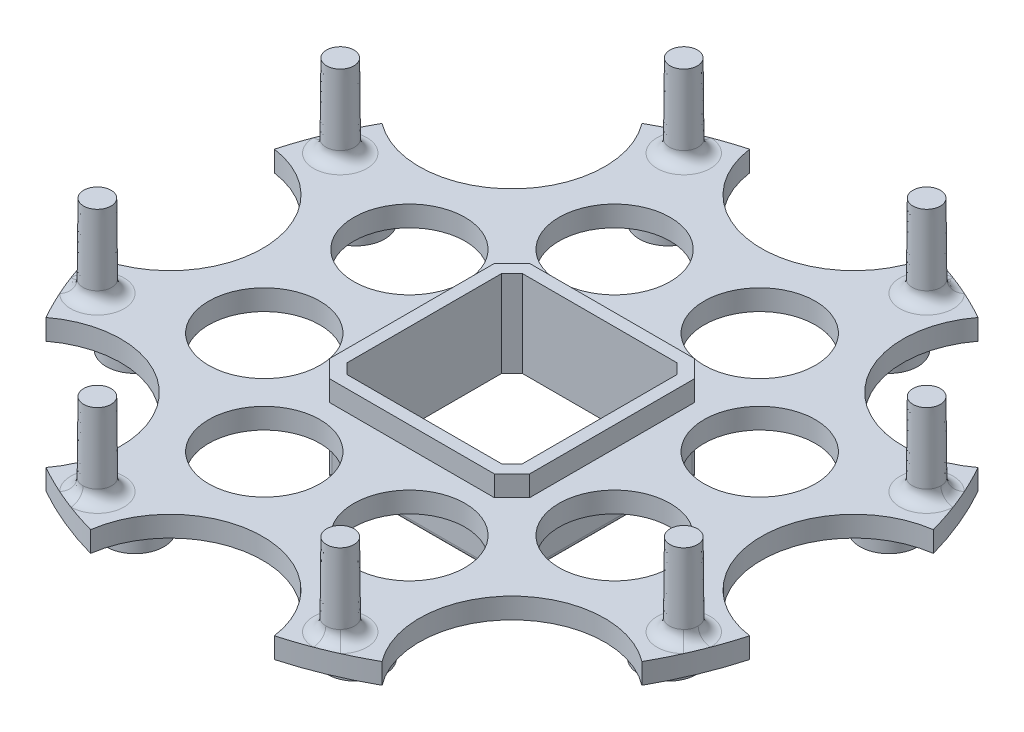
SolidWorks part; units mm, degrees
ref_plane "Front Plane" through (0, 0, 0) normal (0, 0, 1) x (1, 0, 0)
ref_plane "Top Plane" through (0, 0, 0) normal (0, 1, 0) x (1, 0, 0)
ref_plane "Right Plane" through (0, 0, 0) normal (1, 0, 0) x (0, 0, -1)
sketch "Sketch1" plane through (0, 0, 0) normal (0, 1, 0) x (1, 0, 0)
  circle A0 centre (0, 0) radius 83
  dimension "D1" = 166
extrude "Boss-Extrude1" add sketch "Sketch1" along normal blind 5
sketch "Sketch3" plane through (0, 5, 0) normal (0, 1, 0) x (1, 0, 0)
  line L0 (0, 0) -> (-83, 0) construction
  line L1 (0, 0) -> (-71.1387, 29.4666) construction
  circle A0 centre (-71.1387, 29.4666) radius 3.5
  circle A1 centre (0, 0) radius 83 construction
  circle A2 centre (-29.4666, 71.1387) radius 3.5
  circle A3 centre (29.4666, 71.1387) radius 3.5
  circle A4 centre (71.1387, 29.4666) radius 3.5
  circle A5 centre (71.1387, -29.4666) radius 3.5
  circle A6 centre (29.4666, -71.1387) radius 3.5
  circle A7 centre (-29.4666, -71.1387) radius 3.5
  circle A8 centre (-71.1387, -29.4666) radius 3.5
  point P24 (0, 0)
  dimension "D2" = 7
  dimension "D1" = 77
  dimension "D3" = 22.5
  dimension "D4" = 8
extrude "Boss-Extrude2" add sketch "Sketch3" along normal blind 20 draft 0.5 contours A2
sketch "Sketch4" plane through (0, 0, 0) normal (0, -1, 0) x (1, 0, 0)
  line L1 (21.25, -21.25) -> (-21.25, -21.25)
  line L2 (21.25, -21.25) -> (21.25, 21.25)
  line L3 (21.25, 21.25) -> (-21.25, 21.25)
  line L4 (-21.25, -21.25) -> (-21.25, 21.25)
  line L5 (21.25, -21.25) -> (-21.25, 21.25) construction
  line L6 (21.25, 21.25) -> (-21.25, -21.25) construction
  point P0 (0, 0)
  dimension "D1" = 42.5
extrude "Cut-Extrude1" cut sketch "Sketch4" against normal through all
sketch "Sketch5" plane through (0, 0, 0) normal (0, -1, 0) x (1, 0, 0)
  line L0 (0, 0) -> (0, 83) construction
  line L1 (0, 0) -> (31.7627, 76.682) construction
  circle A0 centre (-83, 0) radius 22.5
  circle A1 centre (0, 0) radius 83 construction
  circle A2 centre (-58.6899, 58.6899) radius 22.5
  circle A3 centre (0, 83) radius 22.5
  circle A4 centre (58.6899, 58.6899) radius 22.5
  circle A5 centre (83, 0) radius 22.5
  circle A6 centre (58.6899, -58.6899) radius 22.5
  circle A7 centre (0, -83) radius 22.5
  circle A8 centre (-58.6899, -58.6899) radius 22.5
  circle A9 centre (0, 0) radius 83 construction
  circle A10 centre (17.6034, 42.4985) radius 13.5
  circle A11 centre (42.4985, 17.6034) radius 13.5
  circle A12 centre (42.4985, -17.6034) radius 13.5
  circle A13 centre (17.6034, -42.4985) radius 13.5
  circle A14 centre (-17.6034, -42.4985) radius 13.5
  circle A15 centre (-42.4985, -17.6034) radius 13.5
  circle A16 centre (-42.4985, 17.6034) radius 13.5
  circle A17 centre (-17.6034, 42.4985) radius 13.5
  point P22 (0, 0)
  point P43 (0, 0)
  dimension "D1" = 45
  dimension "D4" = 27
  dimension "D3" = 22.5
  dimension "D5" = 46
  dimension "D2" = 8
  dimension "D6" = 8
extrude "Cut-Extrude2" cut sketch "Sketch5" against normal through all
fillet "Fillet1" radius 3 8 edges at (-71.1387, 5, 32.9666) (29.4666, 5, -67.6387) (-71.1387, 5, -25.9666) (-29.4666, 5, -67.6387) (-29.4666, 5, 74.6387) (29.4666, 5, 74.6387) (71.1387, 5, 32.9666) (71.1387, 5, -25.9666)
chamfer "Chamfer1" distance 2.5 angle 45 4 edges at (-21.25, 2.5, -21.25) (21.25, 2.5, -21.25) (-21.25, 2.5, 21.25) (21.25, 2.5, 21.25)
sketch "Sketch7" plane through (0, 0, 0) normal (0, -1, 0) x (-1, 0, 0)
  line L0 (0, 0) -> (0, -67.5428) construction
  line L1 (0, 0) -> (26.7878, -64.6716) construction
  circle A0 centre (26.7878, -64.6716) radius 7
  circle A1 centre (-26.7878, -64.6716) radius 7
  circle A2 centre (-64.6716, -26.7878) radius 7
  circle A3 centre (-64.6716, 26.7878) radius 7
  circle A4 centre (-26.7878, 64.6716) radius 7
  circle A5 centre (26.7878, 64.6716) radius 7
  circle A6 centre (64.6716, 26.7878) radius 7
  circle A7 centre (64.6716, -26.7878) radius 7
  circle A8 centre (26.7878, -64.6716) radius 2.15
  circle A9 centre (-26.7878, -64.6716) radius 2.15
  circle A10 centre (-64.6716, -26.7878) radius 2.15
  circle A11 centre (-64.6716, 26.7878) radius 2.15
  circle A12 centre (-26.7878, 64.6716) radius 2.15
  circle A13 centre (26.7878, 64.6716) radius 2.15
  circle A14 centre (64.6716, 26.7878) radius 2.15
  circle A15 centre (64.6716, -26.7878) radius 2.15
  point P22 (0, 0)
  point P38 (0, 0)
  dimension "D1" = 14
  dimension "D5" = 4.3
  dimension "D2" = 22.5
  dimension "D3" = 70
  dimension "D4" = 8
  dimension "D6" = 8
extrude "Boss-Extrude3" add sketch "Sketch7" along normal blind 5 contours A3 A11 | A1 A9 | A2 A10 | A0 A8 | A7 A15 | A6 A14 | A5 A13 | A4 A12
sketch "Sketch8" plane through (0, 0, 0) normal (0, -1, 0) x (1, 0, 0)
  line L0 (-18.75, -21.25) -> (-21.25, -18.75) construction
  line L1 (-18.75, -21.25) -> (18.75, -21.25) construction
  line L2 (21.25, -18.75) -> (18.75, -21.25) construction
  line L3 (21.25, -18.75) -> (21.25, 18.75) construction
  line L4 (18.75, 21.25) -> (21.25, 18.75) construction
  line L5 (18.75, 21.25) -> (-18.75, 21.25) construction
  line L6 (-21.25, 18.75) -> (-18.75, 21.25) construction
  line L7 (-21.25, 18.75) -> (-21.25, -18.75) construction
  line L8 (-18.75, -21.25) -> (-21.25, -18.75)
  line L9 (-18.75, -21.25) -> (18.75, -21.25)
  line L10 (21.25, -18.75) -> (18.75, -21.25)
  line L11 (21.25, -18.75) -> (21.25, 18.75)
  line L12 (18.75, 21.25) -> (21.25, 18.75)
  line L13 (18.75, 21.25) -> (-18.75, 21.25)
  line L14 (-21.25, 18.75) -> (-18.75, 21.25)
  line L15 (-21.25, 18.75) -> (-21.25, -18.75)
extrude "Extrude-Thin1" add sketch "Sketch8" along normal blind 11 and the other way blind 10 thin thin type one direction wall 3
fillet "Fillet3" radius 1.25 20 edges at (22.1213, 0, 22.1213) (-22.1213, 0, 22.1213) (-22.1213, 0, -22.1213) (22.1213, 0, -22.1213) (24.25, -5.5, -19.9926) (24.25, -11, 0) (24.25, -5.5, 19.9926) (24.25, 0, 0) (19.9926, -5.5, 24.25) (0, -11, 24.25) (-19.9926, -5.5, 24.25) (0, 0, 24.25) (-24.25, -5.5, 19.9926) (-24.25, -11, 0) (-24.25, -5.5, -19.9926) (-24.25, 0, 0) (-19.9926, -5.5, -24.25) (0, -11, -24.25) (19.9926, -5.5, -24.25) (0, 0, -24.25)
